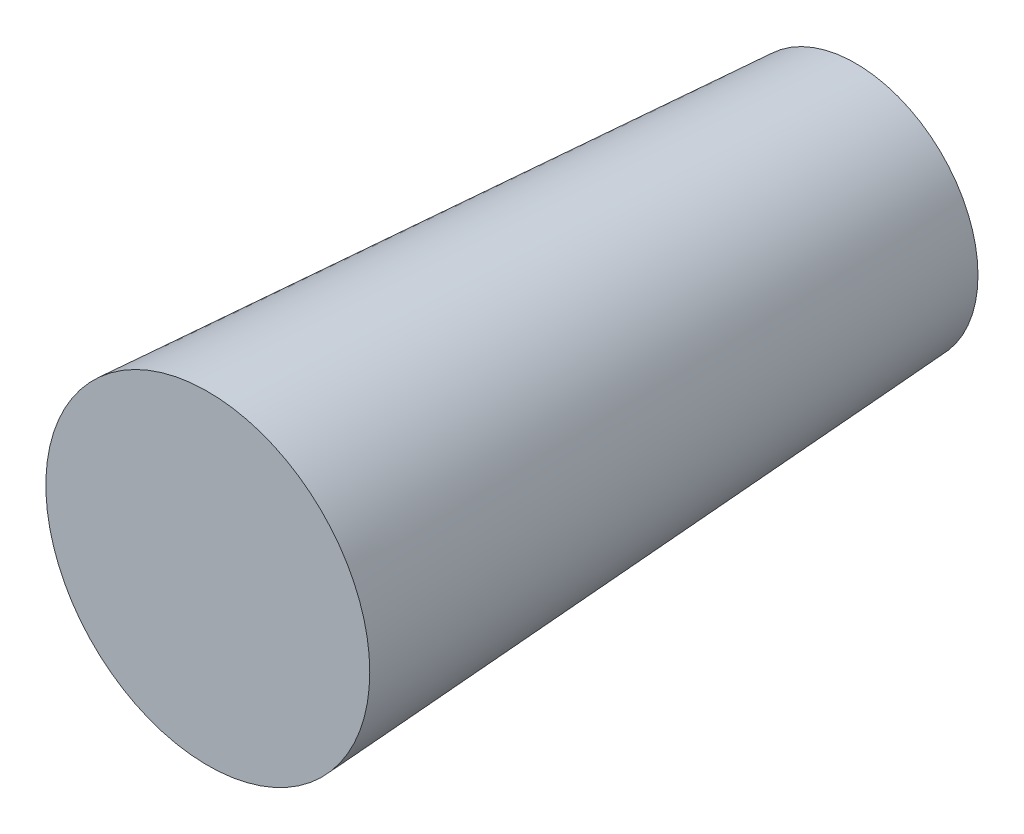
SolidWorks part; units mm, degrees
ref_plane "Front Plane" through (0, 0, 0) normal (0, 0, 1) x (1, 0, 0)
ref_plane "Top Plane" through (0, 0, 0) normal (0, 1, 0) x (1, 0, 0)
ref_plane "Right Plane" through (0, 0, 0) normal (1, 0, 0) x (0, 0, -1)
sketch "Sketch1" plane through (0, 0, 0) normal (0, 0, 1) x (1, 0, 0)
  circle A0 centre (0, 0) radius 3.4
  dimension "D1" = 6.8
ref_plane "Plane1" through (0, 0, 18) normal (0, 0, 1) x (1, 0, 0)
sketch "Sketch2" plane through (0, 0, 18) normal (0, 0, 1) x (1, 0, 0)
  circle A0 centre (0, 0) radius 4.5
  dimension "D1" = 9
loft "Loft1" add profiles "Sketch2", "Sketch1"
